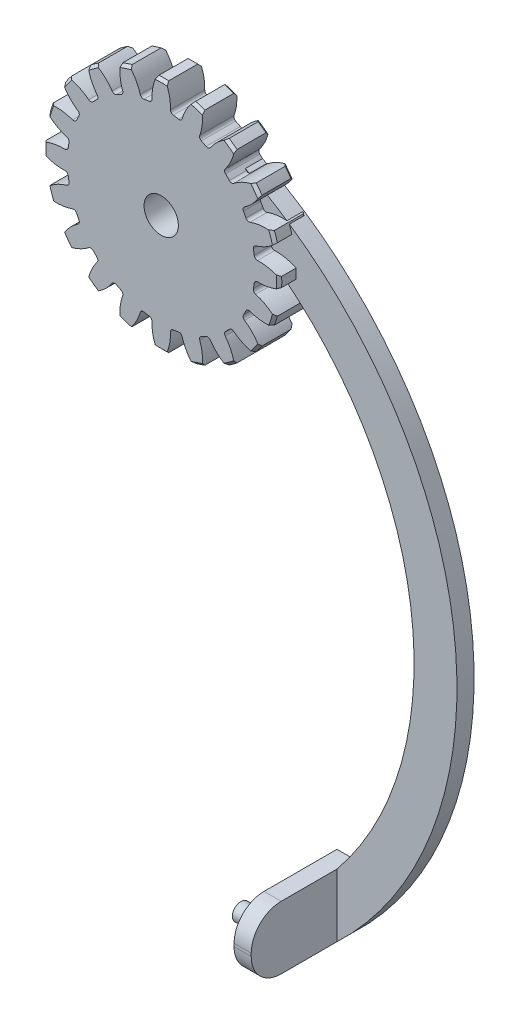
SolidWorks part; units mm, degrees
ref_plane "Front Plane" through (0, 0, 0) normal (0, 0, 1) x (1, 0, 0)
ref_plane "Top Plane" through (0, 0, 0) normal (0, 1, 0) x (1, 0, 0)
ref_plane "Right Plane" through (0, 0, 0) normal (1, 0, 0) x (0, 0, -1)
sketch "Sketch1" plane through (0, 0, 0) normal (0, 0, 1) x (1, 0, 0)
  circle A0 centre (0, 0) radius 12.5 construction
  circle A1 centre (0, 0) radius 13.75
  dimension "D1" = 25
  dimension "D2" = 27.5
extrude "Boss-Extrude1" add sketch "Sketch1" along normal blind 4 contours A1
sketch "Sketch3" plane through (0, 0, 0) normal (0, 0, 1) x (1, 0, 0)
  line L0 (0, 0) -> (0, 13.75) construction
  line L1 (0, 0) -> (-2.151, 13.5807) construction
  line L2 (0, 0) -> (2.151, 13.5807) construction
  line L3 (-2.3599, 10.6799) -> (0, 0) construction
  line L4 (-2.9181, 12.1546) -> (-0.9807, 12.4615) construction
  line L5 (-0.9807, 12.4615) -> (0.9807, 12.4615) construction
  line L6 (-3.5448, 13.2852) -> (-1.5279, 9.6467) construction
  arc A0 (-1.0558, 10.8864) -> (-2.3599, 10.6799) centre (0, 0) ccw
  circle A1 centre (0, 0) radius 11.25 construction
  circle A2 centre (0, 0) radius 13.75 construction
  arc A3 (-3.7081, 13.2406) -> (-2.3599, 10.6799) centre (-7.7122, 9.4972) cw
  circle A4 centre (0, 0) radius 13.75 construction
  arc A5 (-0.5649, 13.7384) -> (-1.0558, 10.8864) centre (4.4, 11.4156) ccw
  circle A6 centre (0, 0) radius 12.5 construction
  arc A7 (-0.5649, 13.7384) -> (-3.7081, 13.2406) centre (0, 0) ccw
  dimension "D1" = 18
  dimension "D2" = 2.5
  dimension "D3" = 2.8125
  dimension "D4" = 20
extrude "Cut-Extrude4" cut sketch "Sketch3" against normal through all and the other way through all
fillet "Fillet1" radius 0.375 2 edges at (-1.0558, 10.8864, 2) (-2.3599, 10.6799, 2)
chamfer "Chamfer1" distance 0.3125 2 edges at (2.151, -13.5807, 0) (2.151, -13.5807, 4)
pattern_circular "CirPattern1" count 20 over 360 about axis through (0, 0, 0) along (0, 0, 1) of "Cut-Extrude4", "Fillet1"
sketch "Sketch4" plane through (0, 0, 4) normal (0, 0, 1) x (1, 0, 0)
  circle A0 centre (0, 0) radius 2
  dimension "D1" = 4
extrude "Cut-Extrude5" cut sketch "Sketch4" against normal through all
sketch "Sketch6" plane through (0, 0, 0) normal (0, 0, 1) x (1, 0, 0)
  line L0 (0, 51.6056) -> (0, -51.6056) construction
  line L1 (12.5, 51.6056) -> (12.5, -51.6056) construction
  line L2 (-12.5, 51.6056) -> (-12.5, -51.6056) construction
  line L3 (-58.6832, 0) -> (52.2435, 0) construction
  line L4 (-23.9113, 12.5) -> (-12.5, 12.5) construction
  line L5 (18.5, 19.9842) -> (18.5, -7.2216) construction
  line L6 (18.5, -57.7784) -> (18.5, -65.119)
  line L7 (0, 12.5) -> (10.24, 12.5) construction
  line L8 (14.5, -83.8484) -> (14.5, -95.4071) construction
  line L9 (0, 10.729) -> (0, 5.4967)
  line L10 (-17.7342, -32.5) -> (-7.4853, -32.5) construction
  circle A0 centre (0, 0) radius 12.5 construction
  arc A1 (18.5, -65.119) -> (0, 10.729) centre (-12.5, -32.5) ccw
  arc A2 (18.5, -57.7784) -> (0, 5.4967) centre (-12.5, -32.5) ccw
  arc A3 (18.5, -65.119) -> (0, 10.729) centre (-12.5, -32.5) ccw
  point P6 (0, 0)
  dimension "D1" = 90
  dimension "D2" = 6
  dimension "D4" = 5.2323
sketch "Sketch7" plane through (0, 0, 0) normal (0, 0, -1) x (-1, 0, 0)
  line L0 (0, 10.729) -> (0, 5.4967)
  line L2 (-18.5, -57.7784) -> (-18.5, -65.119)
  arc A0 (0, 10.729) -> (-18.5, -65.119) centre (12.5, -32.5) ccw
  arc A1 (0, 5.4967) -> (-18.5, -57.7784) centre (12.5, -32.5) ccw
extrude "Boss-Extrude3" add sketch "Sketch7" against normal blind 2
sketch "Sketch8" plane through (18.5, 0, 0) normal (-1, 0, 0) x (0, 0, 1)
  line L0 (2, -57.7784) -> (0, -65.119) construction
  line L1 (0, -57.7784) -> (2, -65.119) construction
  line L2 (8.2, -50.246) -> (8.2, -70.504) construction
  line L3 (0, -57.7784) -> (12, -57.7784)
  line L4 (0, -57.7784) -> (0, -65.119)
  line L5 (0, -65.119) -> (12, -65.119)
  line L6 (12, -57.7784) -> (12, -65.119)
  line L7 (0, -57.7784) -> (12, -65.119) construction
  line L8 (0, -65.119) -> (12, -57.7784) construction
  line L9 (2, -65.119) -> (2, -57.7784) construction
  line L10 (15.4096, -61.4487) -> (1.6184, -61.4487) construction
  point P13 (6, -61.4487)
  dimension "D1" = 7.3406
  dimension "D2" = 12
  dimension "D3" = 6.2
extrude "Boss-Extrude4" add sketch "Sketch8" along normal blind 2
sketch "Sketch9" plane through (16.5, 0, 0) normal (-1, 0, 0) x (0, 0, 1)
  line L0 (15.4096, -61.4487) -> (1.6184, -61.4487) construction
  line L1 (8.2, -50.246) -> (8.2, -70.504) construction
  circle A0 centre (8.2, -61.4487) radius 1
  dimension "D1" = 2
extrude "Boss-Extrude5" add sketch "Sketch9" along normal blind 3
fillet "Fillet3" radius 3.5 2 edges at (17.5, -57.7784, 12) (17.5, -65.119, 12)
equation "\"Module\"= 1.25mm"
equation "\"#teeths\"= 20"
equation "\"Pressure Angle\"= 20"
equation "\"D1@Sketch1\"=\"Module\" * \"#teeths\""
equation "\"D2@Sketch1\"=(\"#teeths\" + 2) * \"Module\""
equation "\"D1@Fillet1\"=0.3 *\"Module\""
equation "\"D1@CirPattern1\"=\"#teeths\""
equation "\"D1@Chamfer1\"=\"Module\" /4"
